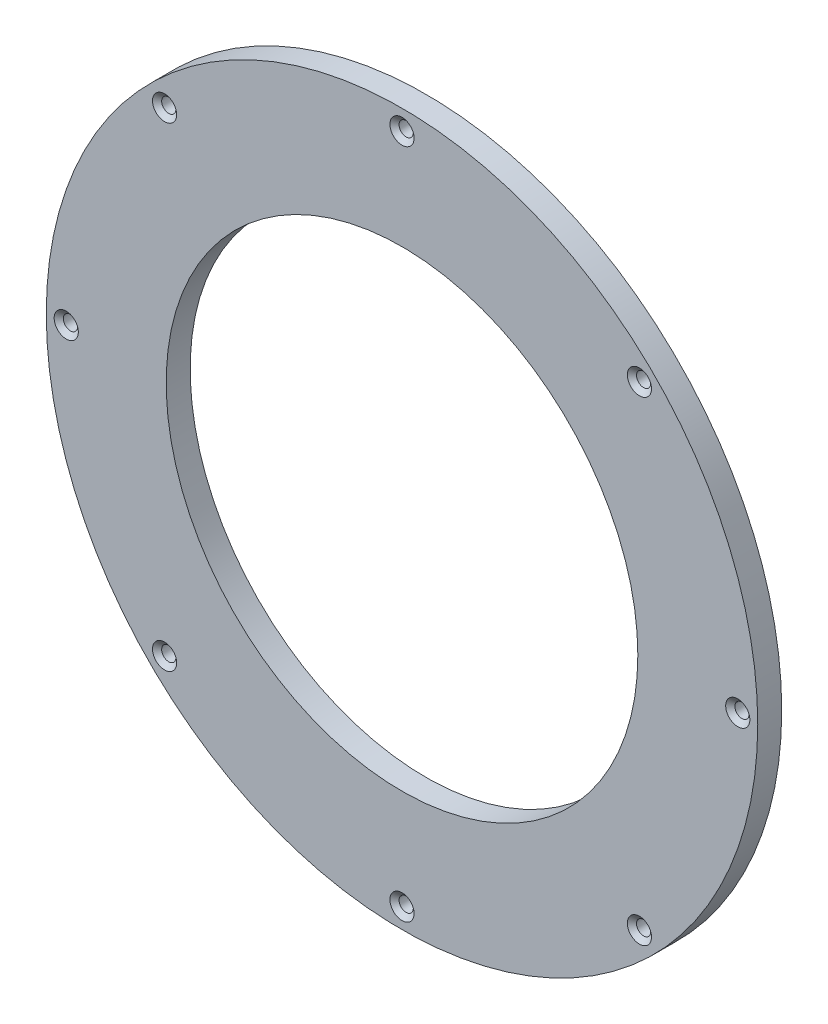
SolidWorks part; units mm, degrees
ref_plane "Front Plane" through (0, 0, 0) normal (0, 0, 1) x (1, 0, 0)
ref_plane "Top Plane" through (0, 0, 0) normal (0, 1, 0) x (1, 0, 0)
ref_plane "Right Plane" through (0, 0, 0) normal (1, 0, 0) x (0, 0, -1)
sketch "Sketch1" plane through (0, 0, 0) normal (0, 0, 1) x (1, 0, 0)
  circle A0 centre (0, 0) radius 44.5
  dimension "D1" = 89
extrude "Boss-Extrude1" add sketch "Sketch1" along normal blind 3
sketch "Sketch2" plane through (0, 0, 3) normal (0, 0, 1) x (1, 0, 0)
  circle A0 centre (0, 0) radius 29.5
  circle A1 centre (0, 0) radius 44.5 construction
  dimension "D1" = 15
extrude "Cut-Extrude1" cut sketch "Sketch2" against normal up to surface (3 mm away) up to face at (44.5, 0, 0)
hole_wizard "CSK for #0 Flat Head Machine Screw (100)1" positions "Sketch3" profile "Sketch4" countersink size "#0" standard "ANSI Inch" end condition through all
sketch "Sketch3" plane through (0, 0, 3) normal (0, 0, 1) x (1, 0, 0)
  circle A0 centre (0, 0) radius 44.5 construction
  point P0 (0, 42)
  dimension "D1" = 42
sketch "Sketch4" plane through (0, 42, 3) normal (1, 0, 0) x (0, -1, 0)
  line L0 (0, 0) -> (0, 3)
  line L1 (0, 3) -> (0.889, 3)
  line L2 (0.889, 3) -> (0.889, 0.5222)
  line L3 (0.889, 0.5222) -> (1.5113, 0)
  line L5 (1.5113, 0) -> (0, 0)
  line L6 (-0.889, 0.5222) -> (-1.5113, 0) construction
  line L11 (0, -6.35) -> (0, 107.95) construction
  dimension "Thru Hole Dia." = 1.778
  dimension "Thru Hole Depth" = 3
  dimension "Near C'Sink Dia." = 3.0226
  dimension "Near C'Sink Angle" = 100
pattern_circular "CirPattern1" count 8 over 360 about axis through (0, 0, 0) along (0, 0, 1) of "CSK for #0 Flat Head Machine Screw (100)1"
